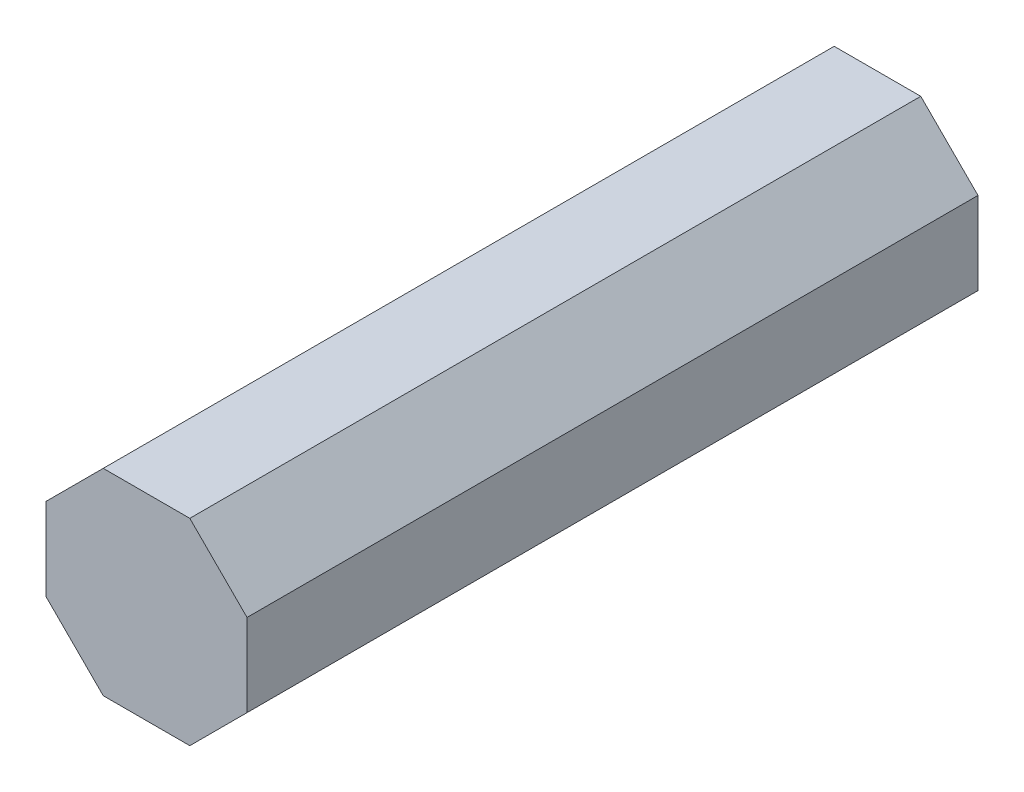
SolidWorks part; units mm, degrees
ref_plane "정면" through (0, 0, 0) normal (0, 0, 1) x (1, 0, 0)
ref_plane "윗면" through (0, 0, 0) normal (0, 1, 0) x (1, 0, 0)
ref_plane "우측면" through (0, 0, 0) normal (1, 0, 0) x (0, 0, -1)
sketch "스케치1" plane through (0, 0, 0) normal (0, 0, 1) x (1, 0, 0)
  line L0 (0, 0) -> (0, 27.1215) construction
  line L1 (-11.8452, 27.1215) -> (11.8452, 27.1215)
  line L2 (11.8452, 27.1215) -> (27.5021, 11.4646)
  line L3 (27.5021, 11.4646) -> (27.5021, -11.0963)
  line L4 (27.5021, -11.0963) -> (11.8452, -26.7532)
  line L5 (11.8452, -26.7532) -> (-11.8452, -26.7532)
  line L6 (-27.5021, -11.0963) -> (-11.8452, -26.7532)
  line L7 (-27.5021, 11.4646) -> (-27.5021, -11.0963)
  line L8 (-11.8452, 27.1215) -> (-27.5021, 11.4646)
  circle A0 centre (0, 0) radius 20 construction
  point P9 (0, -26.7532)
  dimension "D1" = 40
extrude "보스-돌출1" add sketch "스케치1" along normal blind 200
